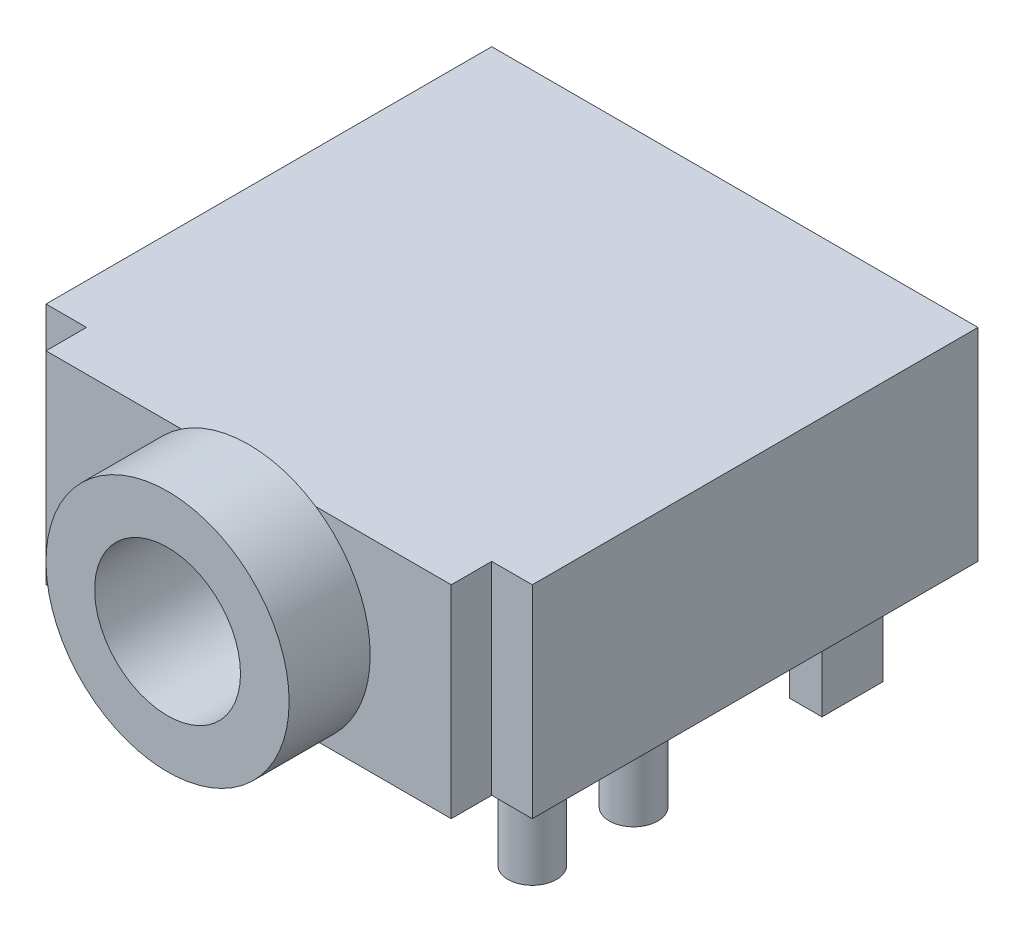
SolidWorks part; units mm, degrees
ref_plane "Спереди" through (0, 0, 0) normal (0, 0, 1) x (1, 0, 0)
ref_plane "Сверху" through (0, 0, 0) normal (0, 1, 0) x (1, 0, 0)
ref_plane "Справа" through (0, 0, 0) normal (1, 0, 0) x (0, 0, -1)
sketch "Эскиз1" plane through (0, 0, 0) normal (0, 0, 1) x (1, 0, 0)
  line L0 (0, 0) -> (0, 11.2175) construction
  line L1 (-6, 0) -> (6, 0)
  line L2 (-6, 0) -> (-6, 5)
  line L3 (-6, 5) -> (6, 5)
  line L4 (6, 0) -> (6, 5)
  line L5 (-6, 0) -> (6, 5) construction
  line L6 (-6, 5) -> (6, 0) construction
  point P0 (0, 2.5)
  dimension "D1" = 5
  dimension "D2" = 12
extrude "Бобышка-Вытянуть1" add sketch "Эскиз1" along normal blind 11
sketch "Эскиз2" plane through (0, 0, 0) normal (0, 1, 0) x (1, 0, 0)
  line L0 (0, 5.2127) -> (0, 2.1123) construction
  line L1 (-6, -11) -> (6, -11) construction
  line L2 (-6, -11) -> (-6, 0) construction
  line L3 (-6, 0) -> (6, 0) construction
  line L4 (6, -11) -> (6, 0) construction
  line L5 (-6, -11) -> (6, 0) construction
  line L6 (-6, 0) -> (6, -11) construction
  line L7 (5, 3.6299) -> (5, -11.6445) construction
  line L9 (4.6, -3.25) -> (5.4, -3.25)
  line L10 (4.6, -3.25) -> (4.6, -1.75)
  line L11 (4.6, -1.75) -> (5.4, -1.75)
  line L12 (5.4, -3.25) -> (5.4, -1.75)
  line L13 (4.6, -3.25) -> (5.4, -1.75) construction
  line L14 (4.6, -1.75) -> (5.4, -3.25) construction
  line L18 (5, -2.5) -> (1.1832, -2.5) construction
  line L19 (2.1, -3.25) -> (2.9, -3.25)
  line L20 (2.1, -3.25) -> (2.1, -1.75)
  line L21 (2.1, -1.75) -> (2.9, -1.75)
  line L22 (2.9, -3.25) -> (2.9, -1.75)
  line L23 (2.1, -3.25) -> (2.9, -1.75) construction
  line L24 (2.1, -1.75) -> (2.9, -3.25) construction
  line L25 (-2.1, -3.25) -> (-2.9, -1.75) construction
  line L26 (-0.75, -7.9) -> (0.75, -7.9)
  line L27 (-0.75, -7.9) -> (-0.75, -7.1)
  line L28 (-0.75, -7.1) -> (0.75, -7.1)
  line L29 (0.75, -7.9) -> (0.75, -7.1)
  line L30 (-0.75, -7.9) -> (0.75, -7.1) construction
  line L31 (-0.75, -7.1) -> (0.75, -7.9) construction
  line L32 (-2.1, -1.75) -> (-2.9, -1.75)
  line L33 (-2.9, -3.25) -> (-2.9, -1.75)
  line L34 (-2.1, -3.25) -> (-2.9, -3.25)
  line L35 (-2.1, -3.25) -> (-2.1, -1.75)
  line L36 (-2.1, -1.75) -> (-2.9, -3.25) construction
  line L37 (-5, -2.5) -> (-1.1832, -2.5) construction
  line L38 (-4.6, -3.25) -> (-5.4, -1.75) construction
  line L39 (-4.6, -1.75) -> (-5.4, -3.25) construction
  line L40 (-4.6, -1.75) -> (-5.4, -1.75)
  line L41 (-5.4, -3.25) -> (-5.4, -1.75)
  line L42 (-4.6, -3.25) -> (-5.4, -3.25)
  line L43 (-4.6, -3.25) -> (-4.6, -1.75)
  line L44 (-5, 3.6299) -> (-5, -11.6445) construction
  circle A0 centre (5, -10) radius 0.6
  circle A1 centre (5, -7.5) radius 0.6
  circle A2 centre (-5, -10) radius 0.6
  circle A3 centre (-5, -7.5) radius 0.6
  point P0 (0, -5.5)
  point P10 (2.5, -2.5)
  point P15 (5, -2.5)
  point P27 (0, -7.5)
  point P47 (0, 0)
  point P48 (-0.1937, -5.5)
  dimension "D6" = 1.2
  dimension "D7" = 1.2
  dimension "D1" = 12
  dimension "D2" = 11
  dimension "D3" = 1
  dimension "D4" = 1
  dimension "D5" = 2.5
  dimension "D8" = 1.5
  dimension "D9" = 0.8
  dimension "D10" = 8.5
  dimension "D11" = 1.5
  dimension "D12" = 0.8
  dimension "D13" = 2.5
  dimension "D14" = 1.5
  dimension "D15" = 0.8
  dimension "D16" = 3.5
extrude "Бобышка-Вытянуть2" add sketch "Эскиз2" against normal blind 2 separate body
sketch "Эскиз3" plane through (0, 0, 11) normal (0, 0, 1) x (1, 0, 0)
  line L0 (-6, 5) -> (6, 0) construction
  line L1 (6, 5) -> (-6, 0) construction
  line L2 (6, 5) -> (-6, 5) construction
  line L3 (-5, 0) -> (5, 0)
  line L4 (-5, 0) -> (-5, 5)
  line L5 (-5, 5) -> (5, 5)
  line L6 (5, 0) -> (5, 5)
  line L7 (-5, 0) -> (5, 5) construction
  line L8 (-5, 5) -> (5, 0) construction
  point P8 (0, 2.5)
  dimension "D1" = 10
extrude "Бобышка-Вытянуть3" add sketch "Эскиз3" along normal blind 1
sketch "Эскиз4" plane through (0, 0, 12) normal (0, 0, 1) x (1, 0, 0)
  line L0 (-5, 5) -> (5, 0) construction
  circle A0 centre (0, 2.5) radius 3
  dimension "D1" = 6
extrude "Бобышка-Вытянуть4" add sketch "Эскиз4" along normal blind 2
sketch "Эскиз5" plane through (0, 0, 14) normal (0, 0, 1) x (1, 0, 0)
  line L0 (0, 5.5) -> (0, -0.5) construction
  circle A0 centre (0, 2.5) radius 3 construction
  circle A1 centre (0, 2.5) radius 1.8
  dimension "D1" = 3.6
extrude "Вырез-Вытянуть1" cut sketch "Эскиз5" against normal up to next (14 mm away)
equation "\"D11@Эскиз2\"=\"D8@Эскиз2\""
equation "\"D12@Эскиз2\"=\"D9@Эскиз2\""
